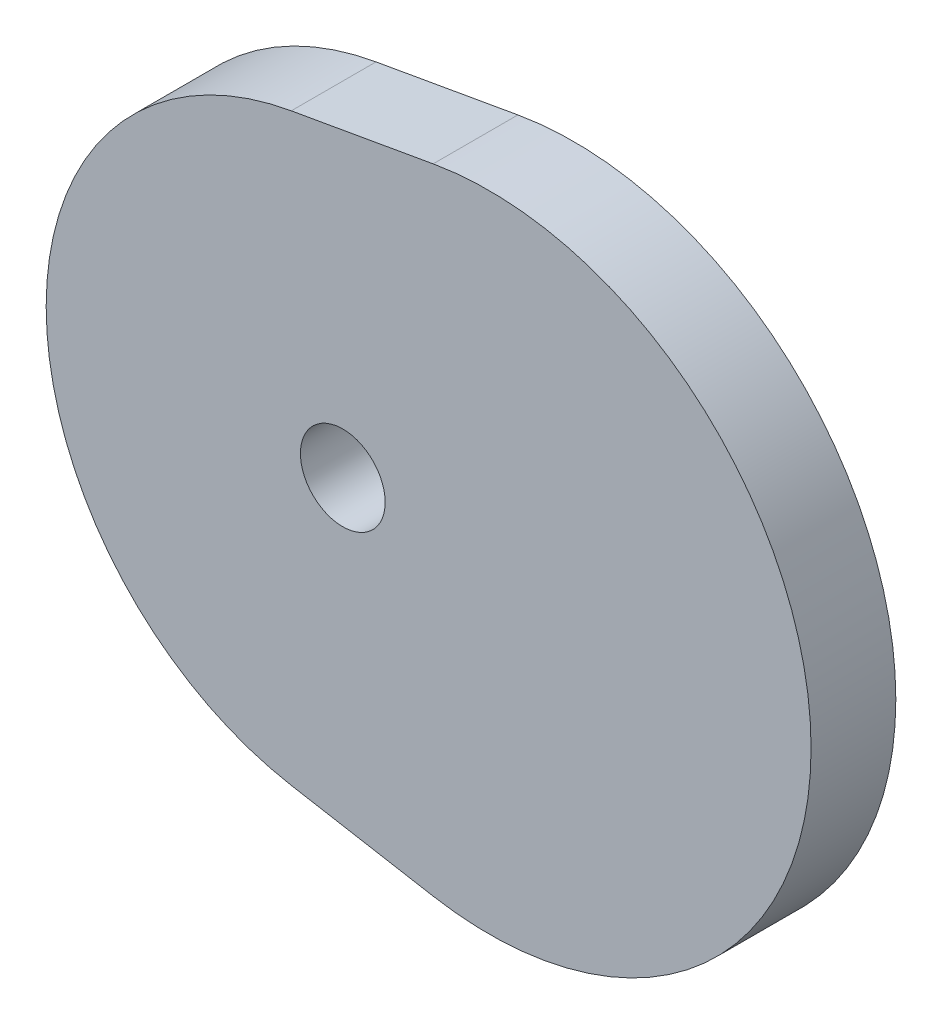
SolidWorks part; units mm, degrees
material "可锻铸铁"
ref_plane "前视基准面" through (0, 0, 0) normal (0, 0, 1) x (1, 0, 0)
ref_plane "上视基准面" through (0, 0, 0) normal (0, 1, 0) x (1, 0, 0)
ref_plane "右视基准面" through (0, 0, 0) normal (1, 0, 0) x (0, 0, -1)
sketch "草图1" plane through (0, 0, 0) normal (0, 0, 1) x (1, 0, 0)
  line L0 (0, 0) -> (98.1048, 0) construction
  line L1 (2.7959, 34.4683) -> (19.5377, 37.4203)
  line L2 (2.7959, -34.4683) -> (19.5377, -37.4203)
  line L3 (2.7959, 34.4683) -> (2.7959, -34.4683) construction
  arc A0 (2.7959, 34.4683) -> (2.7959, -34.4683) centre (8.8736, 0) ccw
  arc A1 (19.5377, 37.4203) -> (19.5377, -37.4203) centre (26.1359, 0) cw
  dimension "D1" = 35
  dimension "D2" = 17
  dimension "D3" = 100
extrude "凸台-拉伸1" add sketch "草图1" along normal blind 10
sketch "草图2" plane through (0, 0, 10) normal (0, 0, 1) x (1, 0, 0)
  circle A0 centre (8.8736, 0) radius 5
  dimension "D1" = 10
extrude "切除-拉伸1" cut sketch "草图2" against normal blind 10
